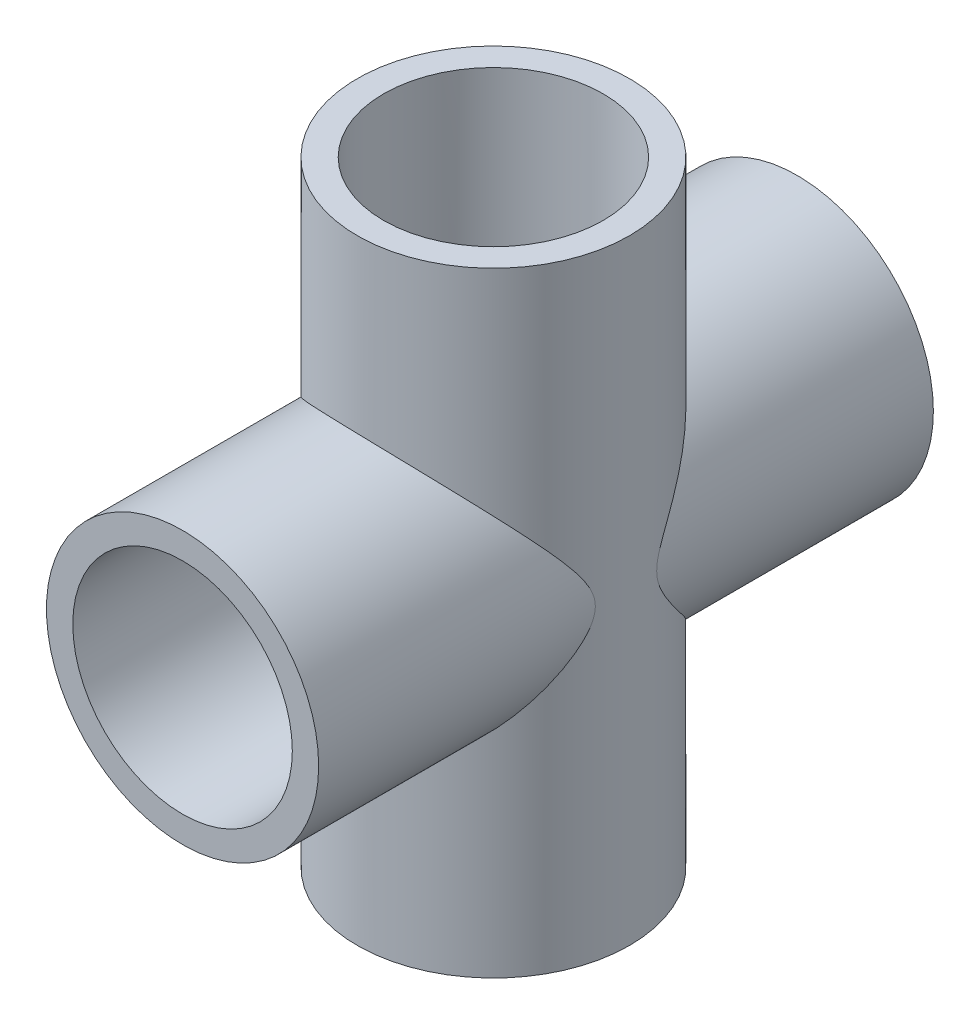
SolidWorks part; units mm, degrees
ref_plane "Front Plane" through (0, 0, 0) normal (0, 0, 1) x (1, 0, 0)
ref_plane "Top Plane" through (0, 0, 0) normal (0, 1, 0) x (1, 0, 0)
ref_plane "Right Plane" through (0, 0, 0) normal (1, 0, 0) x (0, 0, -1)
sketch "Sketch2" plane through (0, 0, 0) normal (0, 0, 1) x (1, 0, 0)
  circle A0 centre (0, 0) radius 125
  dimension "D1" = 250
extrude "Extrude-Thin1" add sketch "Sketch2" along normal blind 700 thin
sketch "Sketch3" plane through (0, 0, 0) normal (0, 1, 0) x (1, 0, 0)
  line L0 (0, 0) -> (7.9828, -700) construction
  line L1 (-155, -700) -> (155, -700) construction
  line L2 (-155, -350) -> (155, -350) construction
  line L3 (-155, 0) -> (-155, -700) construction
  line L4 (155, -700) -> (155, 0) construction
  circle A0 centre (3.9914, -350) radius 125
  dimension "D1" = 250
extrude "Extrude-Thin2" add sketch "Sketch3" along normal mid plane 700 thin
